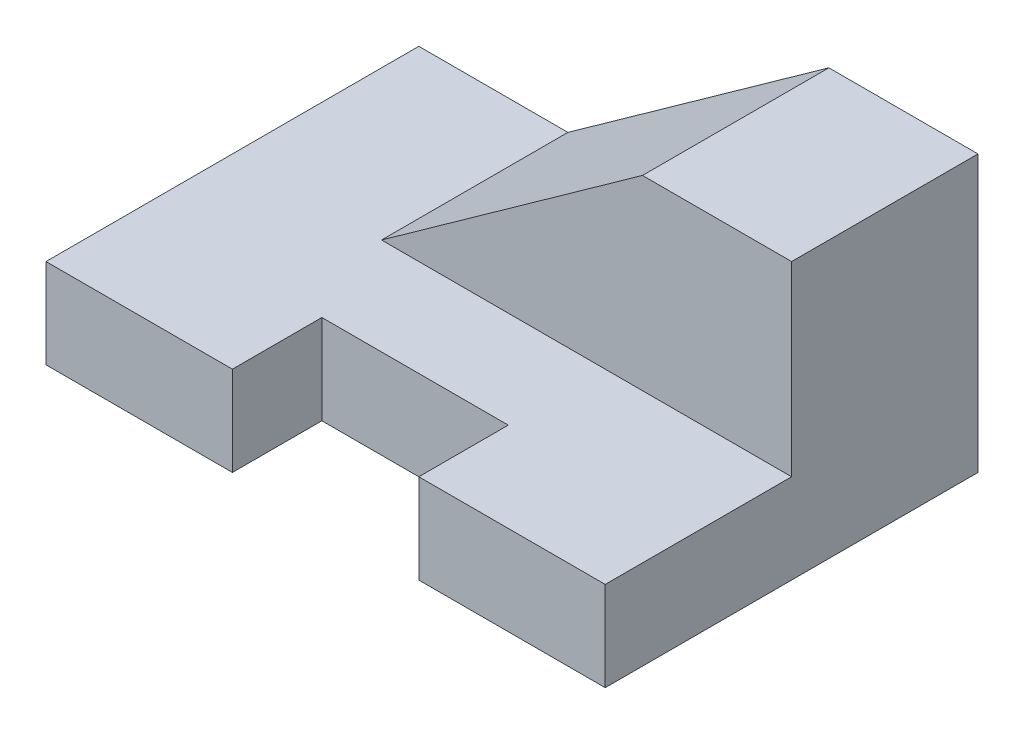
SolidWorks part; units mm, degrees
ref_plane "Front Plane" through (0, 0, 0) normal (0, 0, 1) x (1, 0, 0)
ref_plane "Top Plane" through (0, 0, 0) normal (0, 1, 0) x (1, 0, 0)
ref_plane "Right Plane" through (0, 0, 0) normal (1, 0, 0) x (0, 0, -1)
sketch "Sketch1" plane through (0, 0, 0) normal (0, 1, 0) x (1, 0, 0)
  line L1 (0, 0) -> (75, 0)
  line L2 (0, 0) -> (0, 50)
  line L3 (0, 50) -> (75, 50)
  line L4 (75, 0) -> (75, 50)
  dimension "D1" = 50
  dimension "D2" = 75
extrude "Boss-Extrude1" add sketch "Sketch1" along normal blind 12
sketch "Sketch2" plane through (0, 12, 0) normal (0, 1, 0) x (1, 0, 0)
sketch "Sketch3" plane through (0, 12, 0) normal (0, 1, 0) x (1, 0, 0)
  line L0 (0, 0) -> (75, 0) construction
  line L1 (50, -12) -> (25, -12)
  line L2 (50, -12) -> (50, 12)
  line L3 (50, 12) -> (25, 12)
  line L4 (25, -12) -> (25, 12)
  line L5 (50, -12) -> (25, 12) construction
  line L6 (50, 12) -> (25, -12) construction
  point P0 (37.5, 0)
  dimension "D1" = 25
  dimension "D2" = 24
extrude "Cut-Extrude1" cut sketch "Sketch3" against normal up to next
sketch "Sketch5" plane through (0, 0, -50) normal (0, 0, -1) x (-1, 0, 0)
  line L0 (-75, 12) -> (-75, 37)
  line L1 (-75, 12) -> (0, 12) construction
  line L2 (-75, 37) -> (-55, 37)
  line L3 (-55, 37) -> (-20, 12)
  line L4 (-20, 12) -> (-75, 12)
  dimension "D1" = 25
  dimension "D2" = 20
  dimension "D3" = 55
extrude "Boss-Extrude2" add sketch "Sketch5" against normal blind 25
